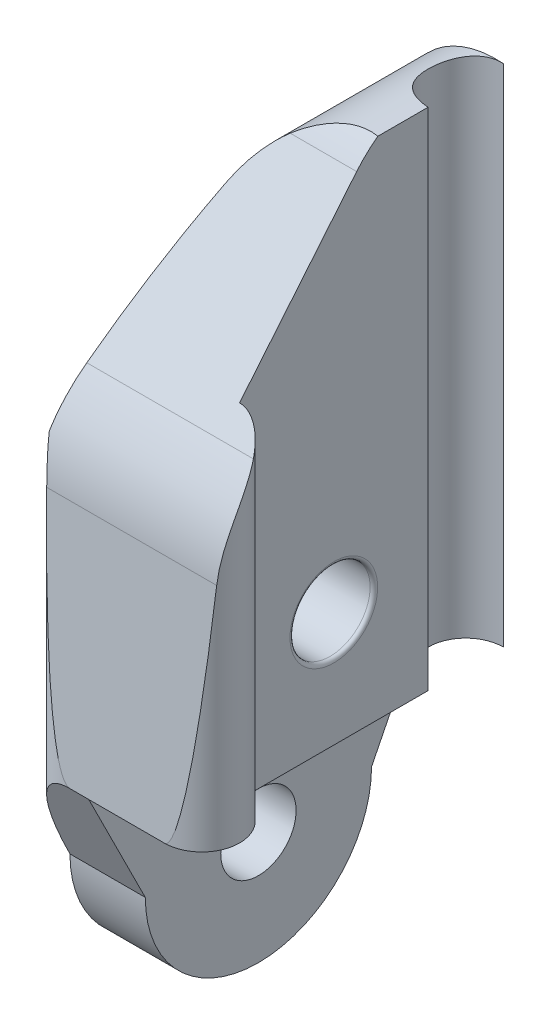
SolidWorks part; units mm, degrees
ref_plane "Front Plane" through (0, 0, 0) normal (0, 0, 1) x (1, 0, 0)
ref_plane "Top Plane" through (0, 0, 0) normal (0, 1, 0) x (1, 0, 0)
ref_plane "Right Plane" through (0, 0, 0) normal (1, 0, 0) x (0, 0, -1)
sketch "Sketch1" plane through (0, 0, 0) normal (0, 1, 0) x (1, 0, 0)
  line L0 (-20.32, 27.0953) -> (-20.32, 11.8553)
  line L1 (0, 27.0953) -> (0, 11.8553)
  line L2 (-16.51, 8.0453) -> (-3.81, 8.0453)
  line L3 (-16.51, 30.9053) -> (-3.81, 30.9053)
  arc A0 (-20.32, 11.8553) -> (-16.51, 8.0453) centre (-16.51, 11.8553) ccw
  arc A1 (-3.81, 8.0453) -> (0, 11.8553) centre (-3.81, 11.8553) ccw
  arc A2 (-20.32, 27.0953) -> (-16.51, 30.9053) centre (-16.51, 27.0953) cw
  arc A3 (0, 27.0953) -> (-3.81, 30.9053) centre (-3.81, 27.0953) ccw
  dimension "D1" = 15.24
  dimension "D2" = 20.32
  dimension "D3" = 22.86
extrude "Boss-Extrude1" add sketch "Sketch1" along normal blind 50.8
sketch "Sketch3" plane through (0, 50.8, 0) normal (0, 1, 0) x (1, 0, 0)
  line L0 (-10.16, 10.5853) -> (-10.16, 28.3653) construction
  line L1 (-16.51, 8.0453) -> (-3.81, 8.0453) construction
  line L2 (-3.81, 30.9053) -> (-16.51, 30.9053) construction
  line L3 (0, 11.8553) -> (0, 27.0953) construction
  circle A0 centre (-10.16, 10.5853) radius 1.27
  circle A1 centre (-10.16, 28.3653) radius 1.27
  dimension "D2" = 2.54
  dimension "D1" = 17.78
  dimension "D3" = 10.16
  dimension "D4" = 2.54
extrude "Cut-Extrude2" cut sketch "Sketch3" against normal blind 50.8 from offset 21.59 offset against normal yes
sketch "Sketch2" plane through (-20.32, 0, 0) normal (-1, 0, 0) x (0, 0, 1)
  line L0 (-27.0953, 7.62) -> (-30.9053, 15.24)
  line L1 (-27.0953, 50.8) -> (-27.0953, 0) construction
  line L2 (-30.9053, 15.24) -> (-30.9053, -5.08)
  line L4 (-8.0453, -5.08) -> (-8.0453, 15.24)
  line L5 (-8.0453, 15.24) -> (-11.8553, 7.62)
  line L6 (-11.8553, 50.8) -> (-11.8553, 0) construction
  line L8 (-27.0953, 0) -> (-11.8553, 0) construction
  line L9 (-30.9053, -5.08) -> (-8.0453, -5.08)
  line L10 (-30.9053, 50.8) -> (-30.9053, 0) construction
  line L11 (-8.0453, 50.8) -> (-8.0453, 0) construction
  arc A0 (-11.8553, 7.62) -> (-27.0953, 7.62) centre (-19.4753, 7.62) cw
  dimension "D1" = 20.32
  dimension "D2" = 5.08
extrude "Cut-Extrude1" cut sketch "Sketch2" against normal blind 50.8
sketch "Sketch4" plane through (0, 0, -8.0453) normal (0, 0, 1) x (1, 0, 0)
  line L0 (-15.24, 15.24) -> (-15.24, 0)
  line L1 (-15.24, 0) -> (-5.08, 0)
  line L2 (-5.08, 0) -> (-5.08, 15.24)
  line L3 (-5.08, 15.24) -> (-15.24, 15.24)
  line L4 (0, 0) -> (0, 7.62) construction
  dimension "D1" = 10.16
  dimension "D2" = 5.08
  dimension "D3" = 15.24
extrude "Cut-Extrude3" cut sketch "Sketch4" against normal blind 50.8
sketch "Sketch5" plane through (-20.32, 0, 0) normal (-1, 0, 0) x (0, 0, 1)
  line L0 (-27.0953, 50.8) -> (-27.0953, 7.62) construction
  circle A0 centre (-19.4753, 7.62) radius 2.54
  arc A1 (-27.0953, 7.62) -> (-11.8553, 7.62) centre (-19.4753, 7.62) ccw construction
  point P5 (-19.4753, 0)
  dimension "D3" = 5.08
  dimension "D1" = 7.62
  dimension "D2" = 7.62
extrude "Cut-Extrude5" cut sketch "Sketch5" against normal blind 50.8
sketch "Sketch6" plane through (-20.32, 0, 0) normal (-1, 0, 0) x (0, 0, 1)
  line L0 (-11.8553, 36.8468) -> (-21.0123, 47.9345)
  line L1 (-27.0953, 50.8) -> (-11.8553, 50.8) construction
  line L2 (-27.0953, 50.8) -> (-31.5254, 50.8)
  line L3 (-11.8553, 50.8) -> (-11.8553, 7.62) construction
  line L4 (-31.5254, 50.8) -> (-31.5254, 15.0885)
  line L5 (-8.0453, 15.24) -> (-9.3575, 30.7255)
  line L6 (-31.5254, 15.0885) -> (-40.3927, 51.9343)
  line L7 (-40.3927, 51.9343) -> (12.2737, 71.2613)
  line L8 (12.2737, 71.2613) -> (-8.0453, 15.24)
  arc A0 (-11.8553, 36.8468) -> (-9.3575, 30.7255) centre (-20.4002, 29.7898) cw
  arc A1 (-21.0123, 47.9345) -> (-27.0953, 50.8) centre (-27.0953, 42.9107) ccw
extrude "Cut-Extrude6" cut sketch "Sketch6" against normal blind 32.512
sketch "Sketch7" plane through (0, 0, -30.9053) normal (0, 0, -1) x (-1, 0, 0)
  line L0 (0, 29.3352) -> (-12.8523, 67.8048)
  line L1 (-12.8523, 67.8048) -> (37.5949, 66.8616)
  line L2 (37.5949, 66.8616) -> (20.32, 29.3352)
  line L3 (0, 50.8) -> (0, 7.62) construction
  line L4 (20.32, 50.8) -> (20.32, 7.62) construction
  arc A0 (0, 29.3352) -> (4.6436, 45.1708) centre (97.9606, 9.2079) cw
  arc A1 (4.6436, 45.1708) -> (16.6823, 45.1708) centre (10.663, 42.851) cw
  arc A2 (16.6823, 45.1708) -> (20.32, 29.3352) centre (-36.8657, 24.5342) cw
extrude "Cut-Extrude7" cut sketch "Sketch7" against normal blind 32.512
sketch "Sketch14" plane through (0, 0, 0) normal (1, 0, 0) x (0, 0, -1)
  line L0 (11.8553, 29.3352) -> (27.0953, 29.3352) construction
  line L1 (11.8553, 29.3352) -> (11.8553, 7.62) construction
  circle A0 centre (19.4753, 22.9852) radius 2.7
  dimension "D1" = 5.4
  dimension "D2" = 6.35
  dimension "D3" = 7.62
extrude "Cut-Extrude12" cut sketch "Sketch14" against normal blind 9.08 from offset 10.16 offset against normal yes
sketch "Sketch8" plane through (0, 15.24, 0) normal (0, -1, 0) x (1, 0, 0)
  line L0 (-10.16, -13.1253) -> (-10.16, -25.8253)
  line L1 (-5.08, -8.0453) -> (-15.24, -8.0453) construction
  line L2 (-5.08, -30.9053) -> (-15.24, -30.9053) construction
  line L3 (-10.16, -8.0453) -> (12.2903, 18.7207)
  line L4 (12.2903, 18.7207) -> (15.1156, -54.0065)
  line L5 (15.1156, -54.0065) -> (-10.16, -30.9053)
  arc A0 (-10.16, -13.1253) -> (-10.16, -8.0453) centre (-10.16, -10.5853) ccw
  arc A1 (-10.16, -25.8253) -> (-10.16, -30.9053) centre (-10.16, -28.3653) ccw
  circle A2 centre (-10.16, -10.5853) radius 1.27 construction
  circle A3 centre (-10.16, -28.3653) radius 1.27 construction
extrude "Cut-Extrude9" cut sketch "Sketch8" against normal mid plane 77.216
sketch "Sketch15" plane through (-20.32, 0, 0) normal (-1, 0, 0) x (0, 0, 1)
  circle A0 centre (-19.4753, 22.9852) radius 2.7
  dimension "D1" = 5.4
extrude "Boss-Extrude2" add sketch "Sketch15" against normal blind 4.2
fillet "Fillet1" radius 0.254 1 edges at (-10.16, 22.9852, -16.7753)
sketch "Sketch16" plane through (-16.12, 0, 0) normal (1, 0, 0) x (0, 0, -1)
  circle A0 centre (19.4753, 22.9852) radius 1.7526
  dimension "D1" = 3.5052
extrude "Cut-Extrude13" cut sketch "Sketch16" against normal blind 3.556
